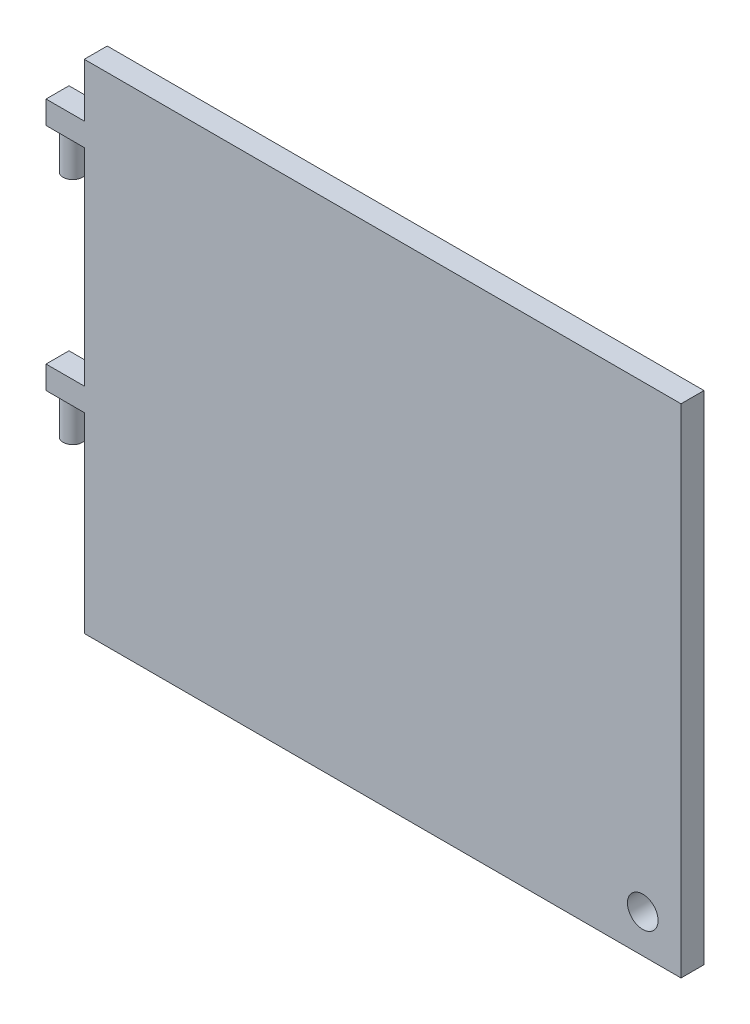
SolidWorks part; units mm, degrees
ref_plane "Ön Düzlem" through (0, 0, 0) normal (0, 0, 1) x (1, 0, 0)
ref_plane "Üst Düzlem" through (0, 0, 0) normal (0, 1, 0) x (1, 0, 0)
ref_plane "Sağ Düzlem" through (0, 0, 0) normal (1, 0, 0) x (0, 0, -1)
sketch "Çizim1" plane through (0, 0, 0) normal (0, 0, 1) x (1, 0, 0)
  line L0 (0, 0) -> (0, 65)
  line L1 (0, 65) -> (78, 65)
  line L2 (78, 65) -> (78, 0)
  line L3 (78, 0) -> (0, 0)
  dimension "D1" = 78
  dimension "D2" = 65
extrude "Yükseklik-Ekstrüzyon1" add sketch "Çizim1" along normal blind 3
sketch "Çizim2" plane through (0, 0, 0) normal (-1, 0, 0) x (0, 0, 1)
  line L0 (3, 65) -> (0, 65) construction
  line L1 (0, 65) -> (0, 0) construction
  line L2 (0, 58) -> (3, 58)
  line L3 (3, 65) -> (3, 0) construction
  line L4 (3, 58) -> (3, 55)
  line L5 (3, 55) -> (0, 55)
  line L6 (0, 55) -> (0, 58)
  line L7 (0, 28) -> (3, 28)
  line L8 (3, 28) -> (3, 25)
  line L9 (3, 25) -> (0, 25)
  line L10 (0, 25) -> (0, 28)
  dimension "D1" = 3
  dimension "D2" = 7
  dimension "D3" = 3
  dimension "D4" = 30
extrude "Yükseklik-Ekstrüzyon2" add sketch "Çizim2" along normal blind 5
sketch "Çizim4" plane through (0, 55, 0) normal (0, -1, 0) x (1, 0, 0)
  circle A0 centre (-3, 1.5) radius 1.25
extrude "Yükseklik-Ekstrüzyon3" add sketch "Çizim4" along normal blind 5
sketch "Çizim5" plane through (0, 25, 0) normal (0, -1, 0) x (1, 0, 0)
  circle A0 centre (-3, 1.5) radius 1.25
extrude "Yükseklik-Ekstrüzyon4" add sketch "Çizim5" along normal blind 5
sketch "Çizim6" plane through (0, 0, 3) normal (0, 0, 1) x (1, 0, 0)
  line L0 (0, 0) -> (78, 0) construction
  line L1 (78, 0) -> (78, 65) construction
  circle A0 centre (73, 5) radius 2
  dimension "D1" = 5
  dimension "D2" = 5
extrude "Kes-Ekstrüzyon2" cut sketch "Çizim6" against normal blind 10 contours A0
